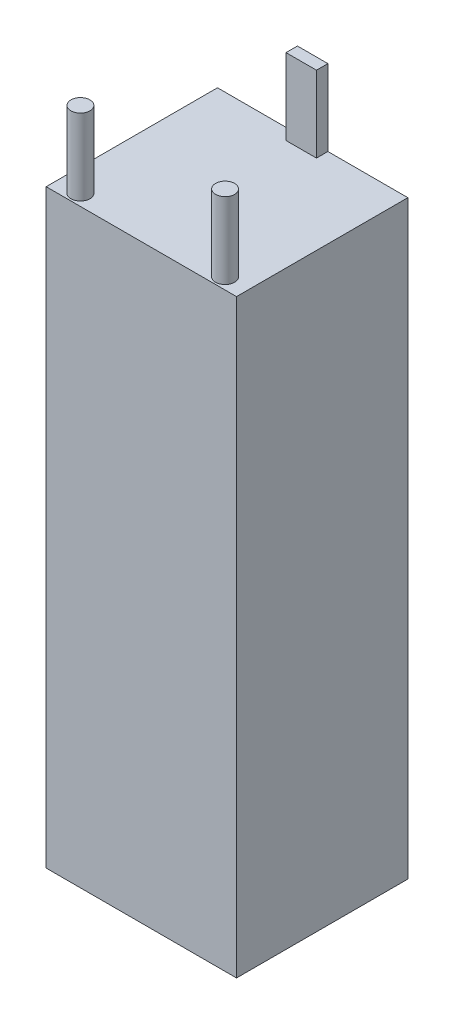
SolidWorks part; units mm, degrees
ref_plane "前视基准面" through (0, 0, 0) normal (0, 0, 1) x (1, 0, 0)
ref_plane "上视基准面" through (0, 0, 0) normal (0, 1, 0) x (1, 0, 0)
ref_plane "右视基准面" through (0, 0, 0) normal (1, 0, 0) x (0, 0, -1)
sketch "草图1" plane through (0, 0, 0) normal (0, 1, 0) x (1, 0, 0)
  line L1 (-25, -22.5) -> (25, -22.5)
  line L2 (-25, -22.5) -> (-25, 22.5)
  line L3 (-25, 22.5) -> (25, 22.5)
  line L4 (25, -22.5) -> (25, 22.5)
  line L5 (-25, -22.5) -> (25, 22.5) construction
  line L6 (-25, 22.5) -> (25, -22.5) construction
  point P0 (0, 0)
  dimension "D1" = 50
  dimension "D2" = 45
extrude "凸台-拉伸1" add sketch "草图1" along normal blind 155
sketch "草图2" plane through (0, 155, 0) normal (0, 1, 0) x (1, 0, 0)
  line L0 (-25, 22.5) -> (-25, -22.5) construction
  line L1 (-25, -22.5) -> (25, -22.5) construction
  line L2 (25, -22.5) -> (25, 22.5) construction
  line L3 (25, 22.5) -> (-25, 22.5) construction
  line L4 (-4, 19.5) -> (4, 19.5)
  line L5 (-4, 19.5) -> (-4, 22.5)
  line L6 (-4, 22.5) -> (4, 22.5)
  line L7 (4, 19.5) -> (4, 22.5)
  line L8 (-4, 19.5) -> (4, 22.5) construction
  line L9 (-4, 22.5) -> (4, 19.5) construction
  circle A0 centre (-19, -19.5) radius 2.5
  circle A1 centre (19, -19.5) radius 2.5
  point P10 (0, 21)
  point P17 (0, 0)
  dimension "D1" = 5
  dimension "D3" = 3
  dimension "D4" = 6
  dimension "D5" = 3
  dimension "D2" = 6
  dimension "D6" = 3
  dimension "D7" = 8
extrude "凸台-拉伸2" add sketch "草图2" along normal blind 20
